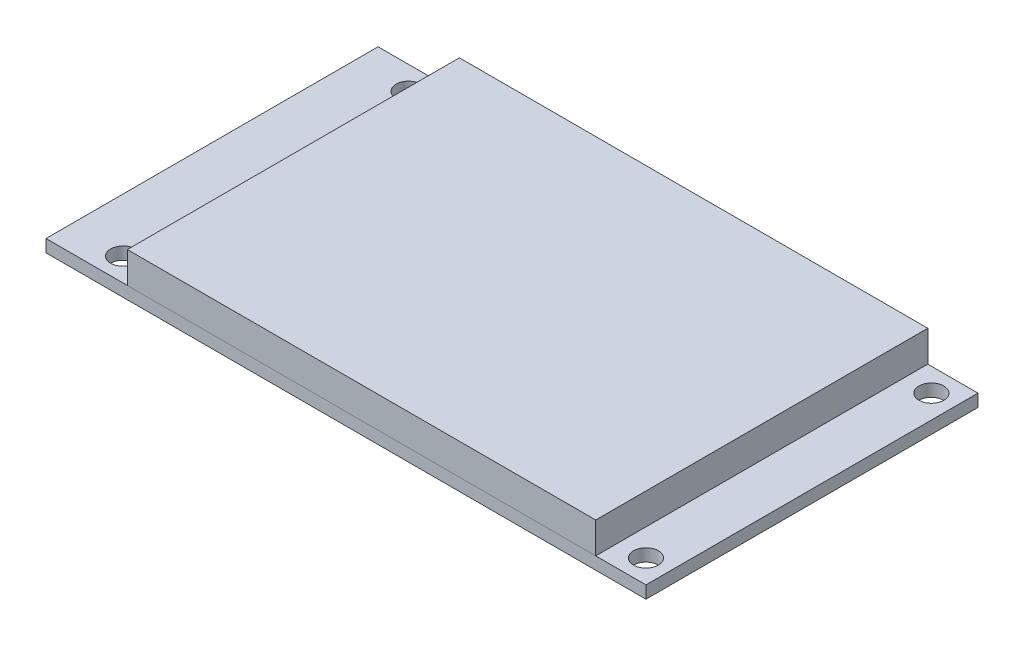
SolidWorks part; units mm, degrees
ref_plane "Płaszczyzna przednia" through (0, 0, 0) normal (0, 0, 1) x (1, 0, 0)
ref_plane "Płaszczyzna górna" through (0, 0, 0) normal (0, 1, 0) x (1, 0, 0)
ref_plane "Płaszczyzna prawa" through (0, 0, 0) normal (1, 0, 0) x (0, 0, -1)
sketch "Szkic1" plane through (0, 0, 0) normal (0, 1, 0) x (1, 0, 0)
  line L0 (-31.67, -21.36) -> (-31.67, 21.36) construction
  line L1 (-38.59, -21.36) -> (38.59, -21.36)
  line L2 (-38.59, -21.36) -> (-38.59, 21.36)
  line L3 (-38.59, 21.36) -> (38.59, 21.36)
  line L4 (38.59, -21.36) -> (38.59, 21.36)
  line L5 (-38.59, -21.36) -> (38.59, 21.36) construction
  line L6 (-38.59, 21.36) -> (38.59, -21.36) construction
  line L7 (35.59, -21.36) -> (35.59, 21.36) construction
  line L8 (-38.59, 0) -> (38.59, 0) construction
  circle A0 centre (-31.67, 18.36) radius 1.6
  circle A1 centre (35.59, 18.36) radius 1.6
  circle A2 centre (35.59, -18.36) radius 1.6
  circle A3 centre (-31.67, -18.36) radius 1.6
  point P0 (0, 0)
  dimension "D5" = 3.2
  dimension "D8" = 3.2
  dimension "D1" = 77.18
  dimension "D2" = 42.72
  dimension "D3" = 6.92
  dimension "D4" = 3
  dimension "D6" = 3
  dimension "D7" = 3
extrude "Dodanie-wyciągnięcie1" add sketch "Szkic1" along normal blind 1.6
sketch "Szkic2" plane through (0, 1.6, 0) normal (0, 1, 0) x (1, 0, 0)
  line L0 (38.59, 21.36) -> (-38.59, 21.36) construction
  line L1 (-28.13, 21.36) -> (32.13, 21.36)
  line L2 (-28.13, 21.36) -> (-28.13, -21.36)
  line L3 (-28.13, -21.36) -> (32.13, -21.36)
  line L4 (32.13, 21.36) -> (32.13, -21.36)
  line L5 (-38.59, -21.36) -> (38.59, -21.36) construction
  line L7 (-38.59, 21.36) -> (-38.59, -21.36) construction
  dimension "D1" = 10.46
  dimension "D2" = 60.26
extrude "Dodanie-wyciągnięcie2" add sketch "Szkic2" along normal blind 4 separate body
